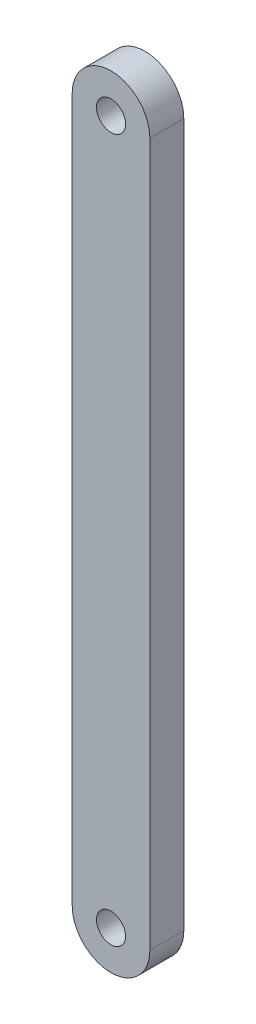
SolidWorks part; units mm, degrees
material "Balsa"
ref_plane "Front Plane" through (0, 0, 0) normal (0, 0, 1) x (1, 0, 0)
ref_plane "Top Plane" through (0, 0, 0) normal (0, 1, 0) x (1, 0, 0)
ref_plane "Right Plane" through (0, 0, 0) normal (1, 0, 0) x (0, 0, -1)
sketch "Sketch1" plane through (0, 0, 0) normal (0, 0, 1) x (1, 0, 0)
  line L0 (0, 0) -> (0, 72.5) construction
  line L1 (-4, 72.5) -> (-4, 0)
  line L2 (4, 0) -> (4, 72.5)
  arc A0 (-4, 72.5) -> (4, 72.5) centre (0, 72.5) cw
  arc A1 (-4, 0) -> (4, 0) centre (0, 0) ccw
  circle A2 centre (0, 72.5) radius 1.5
  circle A3 centre (0, 0) radius 1.5
  dimension "D2" = 4
  dimension "D3" = 3
  dimension "D1" = 72.5
extrude "Boss-Extrude1" add sketch "Sketch1" along normal blind 3.5
